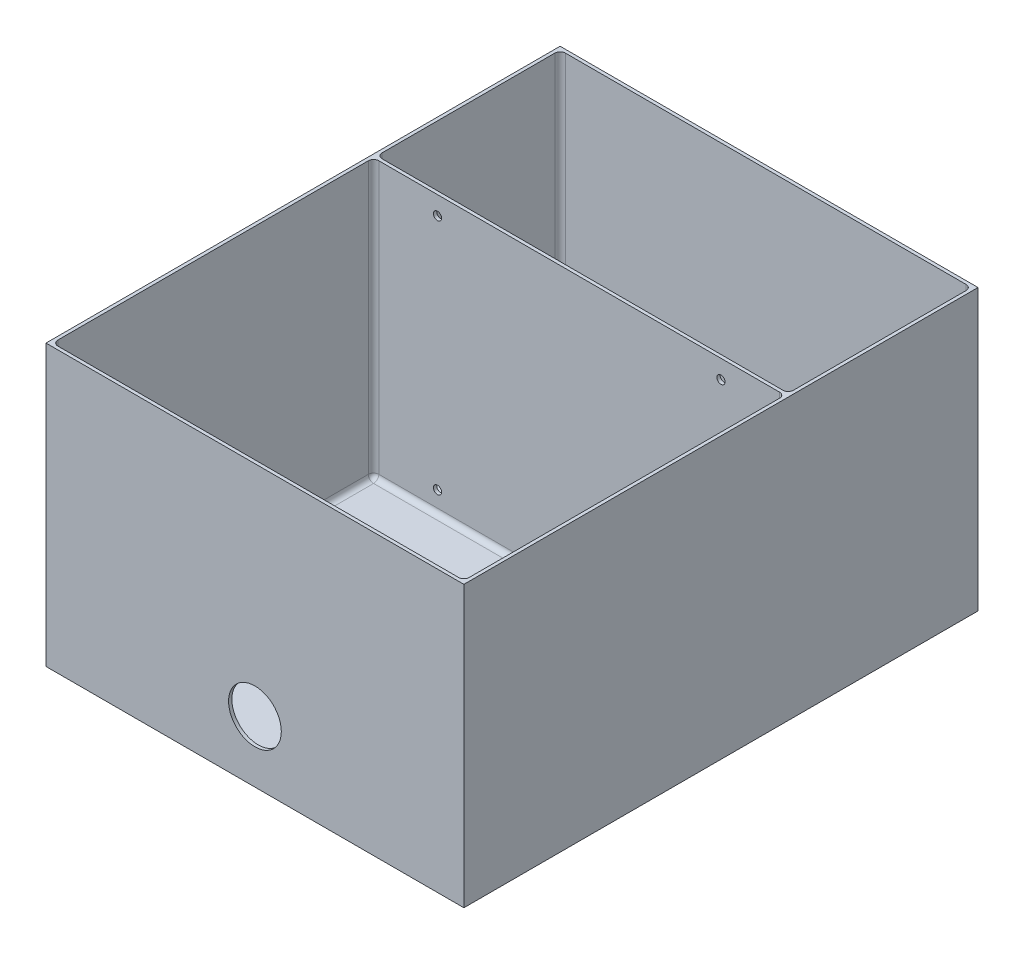
SolidWorks part; units mm, degrees
ref_plane "Front Plane" through (0, 0, 0) normal (0, 0, 1) x (1, 0, 0)
ref_plane "Top Plane" through (0, 0, 0) normal (0, 1, 0) x (1, 0, 0)
ref_plane "Right Plane" through (0, 0, 0) normal (1, 0, 0) x (0, 0, -1)
sketch "Sketch1" plane through (0, 0, 0) normal (0, 1, 0) x (1, 0, 0)
  line L0 (79.25, -36) -> (79.25, 36)
  line L1 (-78, -34.75) -> (78, -34.75)
  line L2 (-78, -34.75) -> (-78, 34.75)
  line L3 (-78, 34.75) -> (78, 34.75)
  line L4 (78, -34.75) -> (78, 34.75)
  line L5 (-78, -34.75) -> (78, 34.75) construction
  line L6 (-78, 34.75) -> (78, -34.75) construction
  line L7 (-79.25, 36) -> (79.25, 36)
  line L8 (-79.25, -36) -> (-79.25, 36)
  line L9 (-78, -36) -> (78, -36)
  line L10 (-78, -36) -> (-78, -86)
  line L11 (-78, -36) -> (78, -36)
  line L12 (-79.25, -36) -> (-79.25, -86)
  line L13 (-79.25, -86) -> (-79.25, -159)
  line L14 (79.25, -36) -> (79.25, -86)
  line L15 (78, -36) -> (78, -86)
  line L16 (-79.25, -36) -> (79.25, -36) construction
  line L17 (-78, -86) -> (-78, -100.5886)
  line L18 (79.25, -86) -> (79.25, -159)
  line L19 (78, -86) -> (78, -157.75)
  line L20 (79.25, -159) -> (-79.25, -159)
  line L21 (78, -159) -> (79.25, -159)
  line L22 (-78, -100.5886) -> (-78, -157.75)
  line L23 (-78, -157.75) -> (78, -157.75)
  line L24 (-78, -157.75) -> (78, -157.75) construction
  line L25 (0, -157.75) -> (0, -117.25)
  line L26 (-40, -117.25) -> (40, -117.25)
  line L27 (-34, -117.25) -> (34, -117.25)
  line L28 (-40, -117.25) -> (-34, -117.25) construction
  circle A0 centre (-37, -117.25) radius 3
  point P0 (0, 0)
  point P27 (0, -117.25)
  point P30 (0, -117.25)
  dimension "D1" = 156
  dimension "D2" = 69.5
  dimension "D4" = 50
  dimension "D5" = 195
  dimension "D6" = 1.25
  dimension "D7" = 40.5
  dimension "D8" = 80
  dimension "D9" = 68
  dimension "D3" = 1.25
sketch "Sketch2" plane through (0, 0, 0) normal (0, 1, 0) x (1, 0, 0)
  line L0 (-79.25, 36) -> (79.25, 36)
  line L1 (79.25, 36) -> (79.25, -159)
  line L2 (79.25, -159) -> (-79.25, -159)
  line L3 (-79.25, -159) -> (-79.25, 36)
extrude "Boss-Extrude1" add sketch "Sketch2" against normal blind 1.25
extrude "Boss-Extrude2" add sketch "Sketch1" along normal blind 105 contours L20 L18 L14 L0 L7 L8 L12 L13 L23 L22 L17 L10 L9 L15 L19 L4 L1 L2 L3
sketch "Sketch4" plane through (0, 0, 0) normal (0, 1, 0) x (1, 0, 0)
  line L0 (-78, -157.75) -> (78, -157.75) construction
  line L1 (0, -157.75) -> (0, -117.75)
  line L2 (0, -58.4375) -> (0, 58.4375) construction
  line L3 (-34, -117.75) -> (34, -117.75)
  line L4 (-40.15, -117.75) -> (-39.575, -117.75)
  line L5 (-40.15, -117.75) -> (-39.575, -117.75) construction
  line L6 (34, -117.75) -> (34.575, -117.75) construction
  line L7 (-34.575, -117.75) -> (34.575, -117.75)
  line L8 (-34.575, -117.75) -> (-34, -117.75) construction
  line L9 (39.575, -117.75) -> (40.15, -117.75) construction
  line L10 (39.575, -117.75) -> (40.15, -117.75)
  circle A0 centre (-37.075, -117.75) radius 2.5
  circle A1 centre (37.075, -117.75) radius 2.5
  point P12 (0, -117.75)
  point P15 (0, -117.75)
  dimension "D1" = 40
  dimension "D2" = 68
  dimension "D3" = 80.3
extrude "Boss-Extrude3" add sketch "Sketch4" along normal blind 8 contours A0 | A1
fillet "Fillet2" radius 2 18 edges at (-78, 0, 0) (0, 0, -34.75) (78, 0, 0) (0, 0, 34.75) (0, 0, 36) (78, 0, 96.875) (0, 0, 157.75) (-78, 0, 96.875) (-37.075, 0, 115.25) (37.075, 0, 115.25) (78, 52.5, -34.75) (-78, 52.5, -34.75) (78, 52.5, 34.75) (-78, 52.5, 34.75) (-78, 52.5, 157.75) (78, 52.5, 157.75) (78, 52.5, 36) (-78, 52.5, 36)
sketch "Sketch5" plane through (0, 0, 36) normal (0, 0, 1) x (1, 0, 0)
  line L0 (-76, 105) -> (76, 105) construction
  line L2 (-76, 105) -> (-76, 2) construction
  line L3 (-58.75, 4.5) -> (58.75, 4.5)
  line L4 (-58.75, 4.5) -> (-58.75, 101.5)
  line L5 (-58.75, 101.5) -> (58.75, 101.5)
  line L6 (58.75, 4.5) -> (58.75, 101.5)
  line L7 (-58.75, 53) -> (58.75, 53)
  line L8 (-53.75, 101.5) -> (-53.75, 98)
  line L14 (-58.75, 98) -> (-53.75, 98)
  line L15 (0, 53) -> (0, 77.907)
  circle A0 centre (-53.75, 98) radius 1.55
  circle A1 centre (-53.75, 8) radius 1.55
  circle A2 centre (53.75, 8) radius 1.55
  circle A3 centre (53.75, 98) radius 1.55
  point P8 (0, 53.5)
  point P29 (0, 0)
  dimension "D1" = 97
  dimension "D2" = 117.5
  dimension "D3" = 17.25
  dimension "D4" = 3.5
  dimension "D5" = 5
  dimension "D6" = 3.5
extrude "Cut-Extrude1" cut sketch "Sketch5" against normal blind 8 contours L14 A0 L8 | L8 A0 L14 | A3 | A1 | A2
sketch "Sketch6" plane through (0, 0, 157.75) normal (0, 0, -1) x (-1, 0, 0)
  line L0 (-76, 2) -> (76, 2) construction
  line L1 (0, 2) -> (0, 22)
  line L2 (0, 58.4375) -> (0, -58.4375) construction
  circle A0 centre (0, 22) radius 10
  dimension "D1" = 20
extrude "Cut-Extrude2" cut sketch "Sketch6" against normal blind 8
sketch "Sketch8" plane through (-79.25, 0, 0) normal (-1, 0, 0) x (0, 0, 1)
  line L0 (159, 62.6576) -> (116.5, 62.6576)
  line L1 (159, -1.25) -> (159, 105) construction
  line L2 (116.5, 20.3153) -> (116.5, 105)
  line L3 (159, 105) -> (-36, 105) construction
  line L4 (116.5, 62.6576) -> (101.5, 62.6576)
  line L5 (116.5, 62.6576) -> (131.5, 62.6576)
  point P9 (116.5, 62.6576)
  dimension "D1" = 42.5
  dimension "D2" = 15
  dimension "D3" = 15
